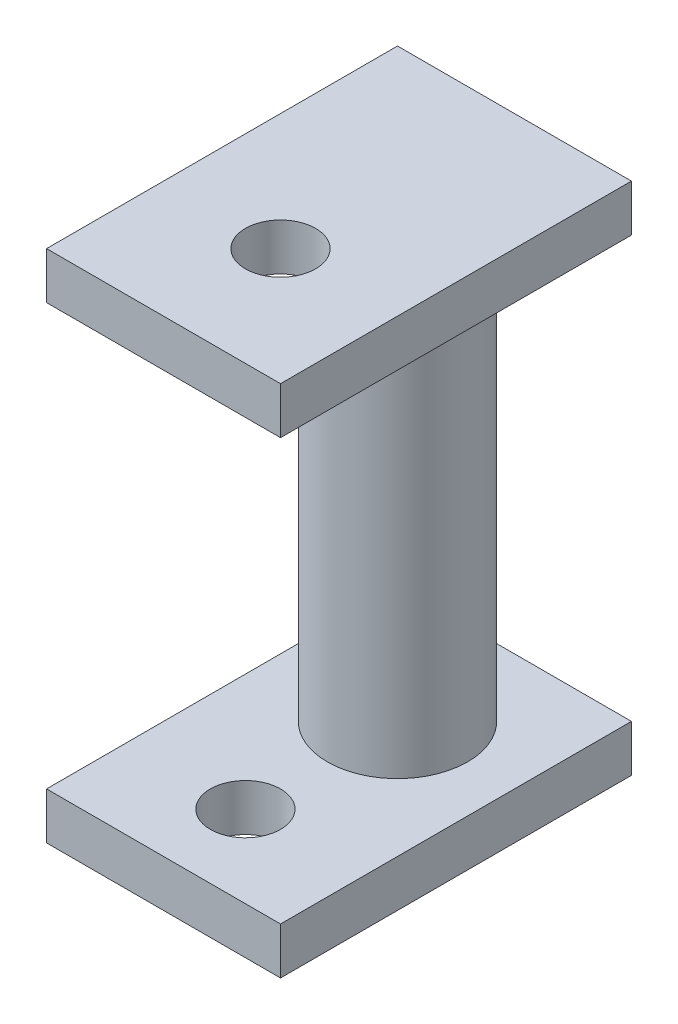
SolidWorks part; units mm, degrees
ref_plane "前视基准面" through (0, 0, 0) normal (0, 0, 1) x (1, 0, 0)
ref_plane "上视基准面" through (0, 0, 0) normal (0, 1, 0) x (1, 0, 0)
ref_plane "右视基准面" through (0, 0, 0) normal (1, 0, 0) x (0, 0, -1)
other "Configuration Table"
sketch "草图1" plane through (0, 0, 0) normal (0, 1, 0) x (1, 0, 0)
  line L1 (-5, -5) -> (5, -5)
  line L2 (-5, -5) -> (-5, 5)
  line L3 (-5, 5) -> (5, 5)
  line L4 (5, -5) -> (5, 5)
  line L5 (-5, -5) -> (5, 5) construction
  line L6 (-5, 5) -> (5, -5) construction
  line L7 (-5, 5) -> (5, 5)
  line L8 (-5, 5) -> (-5, -10)
  line L9 (-5, -10) -> (5, -10)
  line L10 (5, 5) -> (5, -10)
  circle A0 centre (0, 0) radius 3
  circle A1 centre (0, -6.5) radius 1.5
  dimension "D1" = 6
  dimension "D5" = 3
  dimension "D2" = 10
  dimension "D3" = 10
  dimension "D4" = 11.5
  dimension "D6" = 15
extrude "凸台-拉伸2" add sketch "草图1" along normal blind 2 contours L1 L4 L3 L2 A0 | L1 A1 L8 L9 L10 | A0
sketch "草图2" plane through (0, 2, 0) normal (0, 1, 0) x (1, 0, 0)
  circle A0 centre (0, 0) radius 3
extrude "凸台-拉伸3" add sketch "草图2" along normal blind 20
sketch "草图3" plane through (0, 22, 0) normal (0, 1, 0) x (1, 0, 0)
  line L0 (0, 0) -> (0, -5)
  line L2 (-5, -10) -> (5, -10)
  line L3 (-5, -10) -> (-5, 5)
  line L4 (-5, 5) -> (5, 5)
  line L5 (5, -10) -> (5, 5)
  line L6 (-5, -10) -> (5, 5) construction
  line L7 (-5, 5) -> (5, -10) construction
  circle A0 centre (0, 0) radius 1.5
  circle A1 centre (0, -5) radius 1.5
  point P5 (0, -2.5)
  dimension "D1" = 3
  dimension "D3" = 3
  dimension "D2" = 5
  dimension "D4" = 10
  dimension "D5" = 15
extrude "凸台-拉伸4" add sketch "草图3" against normal blind 2
